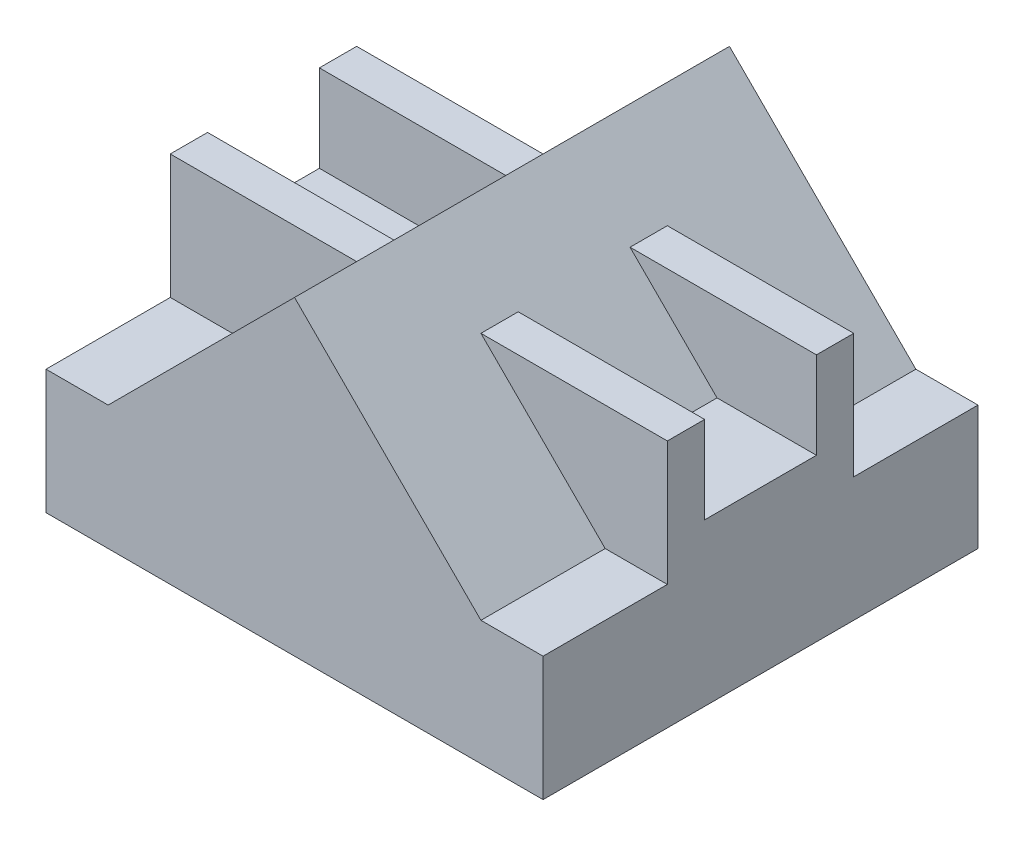
SolidWorks part; units mm, degrees
ref_plane "Front Plane" through (0, 0, 0) normal (0, 0, 1) x (1, 0, 0)
ref_plane "Top Plane" through (0, 0, 0) normal (0, 1, 0) x (1, 0, 0)
ref_plane "Right Plane" through (0, 0, 0) normal (1, 0, 0) x (0, 0, -1)
sketch "Sketch1" plane through (0, 0, 0) normal (0, 0, 1) x (1, 0, 0)
  line L0 (-100, 0) -> (100, 0)
  line L1 (100, 0) -> (100, 100)
  line L2 (100, 100) -> (25, 100)
  line L3 (25, 100) -> (0, 125)
  line L4 (0, 125) -> (-25, 100)
  line L5 (-25, 100) -> (-100, 100)
  line L6 (-100, 100) -> (-100, 0)
  line L7 (0, 0) -> (0, 200) construction
  point P3 (0, 0)
  point P4 (0, 0)
  dimension "D1" = 100
  dimension "D2" = 90
  dimension "D3" = 200
  dimension "D4" = 125
extrude "Boss-Extrude1" add sketch "Sketch1" along normal mid plane 175
sketch "Sketch2" plane through (100, 0, 0) normal (1, 0, 0) x (0, 0, -1)
  line L0 (-87.5, 125) -> (-87.5, 50)
  line L1 (-87.5, 0) -> (-87.5, 100) construction
  line L2 (-87.5, 50) -> (-37.5, 50)
  line L3 (0, 0) -> (0, 135.3117) construction
  line L4 (-37.5, 50) -> (-37.5, 100)
  line L5 (-87.5, 100) -> (87.5, 100) construction
  line L6 (-37.5, 100) -> (-22.5, 100)
  line L7 (-22.5, 100) -> (-22.5, 65)
  line L8 (-22.5, 65) -> (22.5, 65)
  line L9 (22.5, 65) -> (22.5, 100)
  line L10 (22.5, 100) -> (37.5, 100)
  line L11 (37.5, 100) -> (37.5, 50)
  line L12 (37.5, 50) -> (87.5, 50)
  line L13 (87.5, 0) -> (87.5, 100) construction
  line L14 (87.5, 50) -> (87.5, 125)
  line L15 (87.5, 125) -> (-87.5, 125)
  line L16 (-87.5, 0) -> (87.5, 0) construction
  point P9 (27.1196, 100)
  dimension "D1" = 50
  dimension "D2" = 15
  dimension "D3" = 50
  dimension "D4" = 65
extrude "Cut-Extrude1" cut sketch "Sketch2" against normal up to surface (175 mm away)
sketch "Sketch3" plane through (-100, 0, 0) normal (-1, 0, 0) x (0, 0, 1)
  line L12 (-22.5, 100) -> (-22.5, 65)
  line L13 (-37.5, 100) -> (-22.5, 100)
  line L14 (-37.5, 50) -> (-37.5, 100)
  line L15 (-87.5, 50) -> (-37.5, 50)
  line L16 (-87.5, 125) -> (-87.5, 50)
  line L17 (87.5, 125) -> (-87.5, 125)
  line L18 (87.5, 50) -> (87.5, 125)
  line L19 (37.5, 50) -> (87.5, 50)
  line L20 (37.5, 100) -> (37.5, 50)
  line L21 (22.5, 100) -> (37.5, 100)
  line L22 (22.5, 65) -> (22.5, 100)
  line L23 (-22.5, 65) -> (22.5, 65)
  line L24 (-22.5, 100) -> (-22.5, 65)
  line L25 (-37.5, 100) -> (-22.5, 100)
  line L26 (-37.5, 50) -> (-37.5, 100)
  line L27 (-87.5, 50) -> (-37.5, 50)
  line L28 (-87.5, 125) -> (-87.5, 50)
  line L29 (87.5, 125) -> (-87.5, 125)
  line L30 (87.5, 50) -> (87.5, 125)
  line L31 (37.5, 50) -> (87.5, 50)
  line L32 (37.5, 100) -> (37.5, 50)
  line L33 (22.5, 100) -> (37.5, 100)
  line L34 (22.5, 65) -> (22.5, 100)
  line L35 (-22.5, 65) -> (22.5, 65)
  dimension "D1" = 0
extrude "Cut-Extrude2" cut sketch "Sketch3" against normal up to surface (75 mm away)
